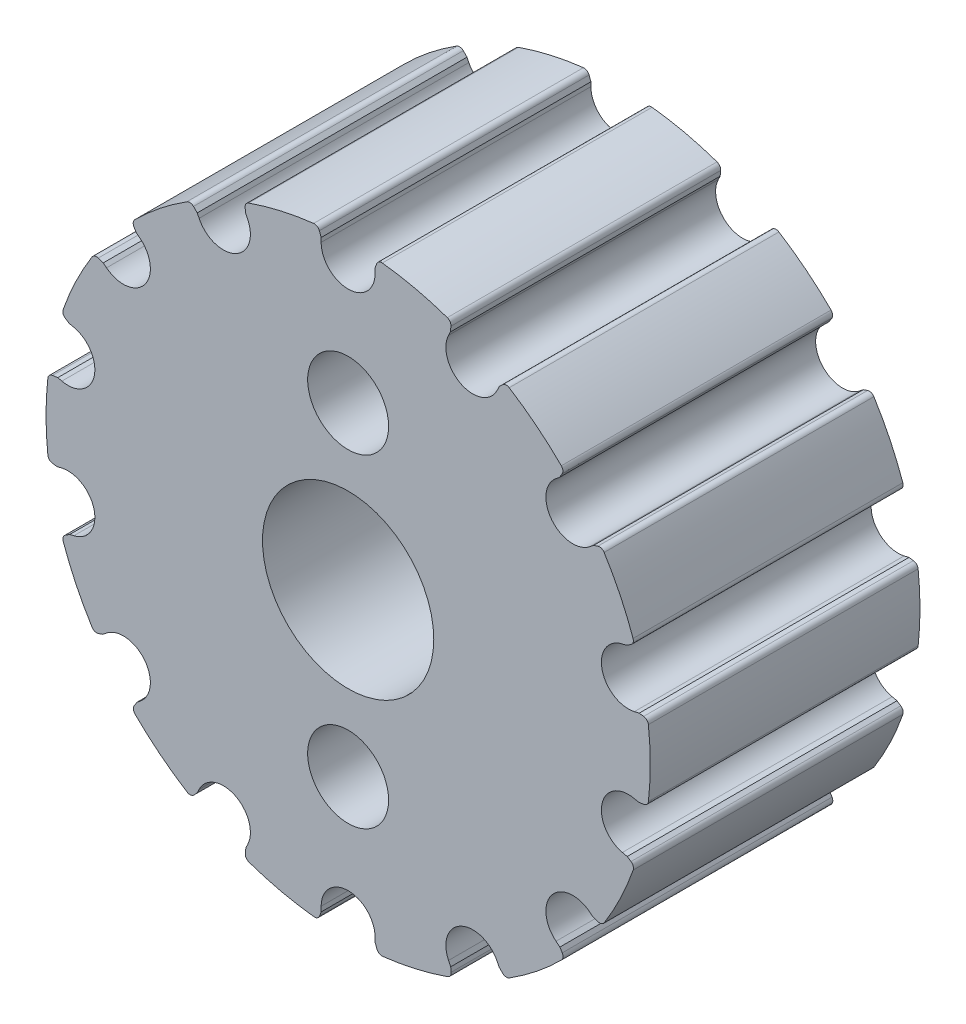
SolidWorks part; units mm, degrees
ref_plane "Спереди" through (0, 0, 0) normal (0, 0, 1) x (1, 0, 0)
ref_plane "Сверху" through (0, 0, 0) normal (0, 1, 0) x (1, 0, 0)
ref_plane "Справа" through (0, 0, 0) normal (1, 0, 0) x (0, 0, -1)
sketch "Эскиз1" plane through (0, 0, 0) normal (0, 0, 1) x (1, 0, 0)
  line L0 (0, 0) -> (0, 13.132) construction
  line L1 (-0.6859, 9.95) -> (0, 9.95)
  line L2 (0, 9.95) -> (0.676, 9.95)
  line L3 (-0.6859, 9.95) -> (-1.1204, 11.1438)
  line L4 (0, 11.2) -> (1.7516, 11.2) construction
  line L5 (3.6991, 9.2623) -> (3.8256, 10.5264)
  line L6 (1.1109, 11.1448) -> (0.676, 9.95)
  line L7 (3.6991, 9.2623) -> (4.3171, 8.9646)
  line L8 (4.3171, 8.9646) -> (4.9262, 8.6713)
  line L9 (5.8364, 9.5591) -> (4.9262, 8.6713)
  line L10 (7.3516, 6.74) -> (8.014, 7.8241)
  line L11 (7.3516, 6.74) -> (7.7792, 6.2037)
  line L12 (7.7792, 6.2037) -> (8.2007, 5.6752)
  line L13 (9.4059, 6.0801) -> (8.2007, 5.6752)
  line L14 (9.5479, 2.8828) -> (10.6151, 3.5721)
  line L15 (9.5479, 2.8828) -> (9.7005, 2.2141)
  line L16 (9.7005, 2.2141) -> (9.851, 1.555)
  line L17 (11.1125, 1.3969) -> (9.851, 1.555)
  line L18 (9.8532, -1.5453) -> (11.1137, -1.3874)
  line L19 (9.8532, -1.5453) -> (9.7005, -2.2141)
  line L20 (9.7005, -2.2141) -> (9.5501, -2.8731)
  line L21 (10.6182, -3.563) -> (9.5501, -2.8731)
  line L22 (8.2069, -5.6674) -> (9.4112, -6.0721)
  line L23 (8.2069, -5.6674) -> (7.7792, -6.2037)
  line L24 (7.7792, -6.2037) -> (7.3577, -6.7322)
  line L25 (8.0207, -7.8172) -> (7.3577, -6.7322)
  line L26 (4.9351, -8.667) -> (5.8446, -9.5541)
  line L27 (4.9351, -8.667) -> (4.3171, -8.9646)
  line L28 (4.3171, -8.9646) -> (3.7081, -9.2579)
  line L29 (3.8347, -10.5231) -> (3.7081, -9.2579)
  line L30 (0.6859, -9.95) -> (1.1204, -11.1438)
  line L31 (0.6859, -9.95) -> (0, -9.95)
  line L32 (0, -9.95) -> (-0.676, -9.95)
  line L33 (-1.1109, -11.1448) -> (-0.676, -9.95)
  line L34 (-3.6991, -9.2623) -> (-3.8256, -10.5264)
  line L35 (-3.6991, -9.2623) -> (-4.3171, -8.9646)
  line L36 (-4.3171, -8.9646) -> (-4.9262, -8.6713)
  line L37 (-5.8364, -9.5591) -> (-4.9262, -8.6713)
  line L38 (-7.3516, -6.74) -> (-8.014, -7.8241)
  line L39 (-7.3516, -6.74) -> (-7.7792, -6.2037)
  line L40 (-7.7792, -6.2037) -> (-8.2007, -5.6752)
  line L41 (-9.4059, -6.0801) -> (-8.2007, -5.6752)
  line L42 (-9.5479, -2.8828) -> (-10.6151, -3.5721)
  line L43 (-9.5479, -2.8828) -> (-9.7005, -2.2141)
  line L44 (-9.7005, -2.2141) -> (-9.851, -1.555)
  line L45 (-11.1125, -1.3969) -> (-9.851, -1.555)
  line L46 (-9.8532, 1.5453) -> (-11.1137, 1.3874)
  line L47 (-9.8532, 1.5453) -> (-9.7005, 2.2141)
  line L48 (-9.7005, 2.2141) -> (-9.5501, 2.8731)
  line L49 (-10.6182, 3.563) -> (-9.5501, 2.8731)
  line L50 (-8.2069, 5.6674) -> (-9.4112, 6.0721)
  line L51 (-8.2069, 5.6674) -> (-7.7792, 6.2037)
  line L52 (-7.7792, 6.2037) -> (-7.3577, 6.7322)
  line L53 (-8.0207, 7.8172) -> (-7.3577, 6.7322)
  line L54 (-4.9351, 8.667) -> (-5.8446, 9.5541)
  line L55 (-4.9351, 8.667) -> (-4.3171, 8.9646)
  line L56 (-4.3171, 8.9646) -> (-3.7081, 9.2579)
  line L57 (-3.8347, 10.5231) -> (-3.7081, 9.2579)
  line L114 (0, 9.95) -> (0, 22.3219) construction
  arc A0 (3.8256, 10.5264) -> (1.1109, 11.1448) centre (0, 0) ccw
  circle A1 centre (0, 0) radius 2.5
  circle A2 centre (0, 6) radius 1.5
  circle A3 centre (0, -6) radius 1.5
  arc A4 (8.014, 7.8241) -> (5.8364, 9.5591) centre (0, 0) ccw
  arc A5 (10.6151, 3.5721) -> (9.4059, 6.0801) centre (0, 0) ccw
  arc A6 (11.1137, -1.3874) -> (11.1125, 1.3969) centre (0, 0) ccw
  arc A7 (9.4112, -6.0721) -> (10.6182, -3.563) centre (0, 0) ccw
  arc A8 (5.8446, -9.5541) -> (8.0207, -7.8172) centre (0, 0) ccw
  arc A9 (1.1204, -11.1438) -> (3.8347, -10.5231) centre (0, 0) ccw
  arc A10 (-3.8256, -10.5264) -> (-1.1109, -11.1448) centre (0, 0) ccw
  arc A11 (-8.014, -7.8241) -> (-5.8364, -9.5591) centre (0, 0) ccw
  arc A12 (-10.6151, -3.5721) -> (-9.4059, -6.0801) centre (0, 0) ccw
  arc A13 (-11.1137, 1.3874) -> (-11.1125, -1.3969) centre (0, 0) ccw
  arc A14 (-9.4112, 6.0721) -> (-10.6182, 3.563) centre (0, 0) ccw
  arc A15 (-5.8446, 9.5541) -> (-8.0207, 7.8172) centre (0, 0) ccw
  arc A16 (-1.1204, 11.1438) -> (-3.8347, 10.5231) centre (0, 0) ccw
  dimension "D4" = 40
  dimension "D6" = 1.25
  dimension "D7" = 22.4
  dimension "D8" = 6
  dimension "D3" = 0.676
  dimension "D5" = 110
extrude "Вытянуть1" add sketch "Эскиз1" along normal blind 10
fillet "Скругление1" radius 0.2 55 edges at (-9.5479, -2.8828, 5) (-10.6151, -3.5721, 5) (-7.3516, -6.74, 5) (-8.014, -7.8241, 5) (-11.1125, -1.3969, 5) (-9.851, -1.555, 5) (-9.4059, -6.0801, 5) (-8.2007, -5.6752, 5) (-5.8364, -9.5591, 5) (-4.9262, -8.6713, 5) (-3.6991, -9.2623, 5) (-3.8256, -10.5264, 5) (1.1204, -11.1438, 5) (0.6859, -9.95, 5) (-1.1109, -11.1448, 5) (-0.676, -9.95, 5) (4.9351, -8.667, 5) (5.8446, -9.5541, 5) (3.8347, -10.5231, 5) (3.7081, -9.2579, 5) (8.0207, -7.8172, 5) (7.3577, -6.7322, 5) (8.2069, -5.6674, 5) (9.4112, -6.0721, 5) (9.8532, -1.5453, 5) (11.1137, -1.3874, 5) (10.6182, -3.563, 5) (9.5501, -2.8731, 5) (11.1125, 1.3969, 5) (9.851, 1.555, 5) (9.5479, 2.8828, 5) (10.6151, 3.5721, 5) (8.014, 7.8241, 5) (7.3516, 6.74, 5) (9.4059, 6.0801, 5) (8.2007, 5.6752, 5) (3.6991, 9.2623, 5) (3.8256, 10.5264, 5) (5.8364, 9.5591, 5) (4.9262, 8.6713, 5) (-0.6859, 9.95, 5) (-1.1204, 11.1438, 5) (1.1109, 11.1448, 5) (0.676, 9.95, 5) (-4.9351, 8.667, 5) (-5.8446, 9.5541, 5) (-3.8347, 10.5231, 5) (-3.7081, 9.2579, 5) (-8.0207, 7.8172, 5) (-7.3577, 6.7322, 5) (-11.1137, 1.3874, 5) (-9.8532, 1.5453, 5) (-10.6182, 3.563, 5) (-9.4112, 6.0721, 5) (-8.2069, 5.6674, 5)
sketch "Эскиз2" plane through (0, 0, 10) normal (0, 0, 1) x (1, 0, 0)
  line L0 (0, 0) -> (0, 13.8774) construction
  line L1 (4.7401, 12.1477) -> (6.542, 11.2799)
  line L2 (-1, 13.0013) -> (1, 13.0013)
  line L3 (-1, 13.0013) -> (-1, 10.6564)
  line L4 (4.7401, 12.1477) -> (3.7227, 10.035)
  line L5 (1, 13.0013) -> (1, 10.6564)
  line L6 (6.542, 11.2799) -> (5.5246, 9.1672)
  line L7 (9.5414, 8.888) -> (10.7884, 7.3244)
  line L8 (9.5414, 8.888) -> (7.708, 7.426)
  line L9 (10.7884, 7.3244) -> (8.955, 5.8623)
  line L10 (12.4529, 3.868) -> (12.8979, 1.9181)
  line L11 (12.4529, 3.868) -> (10.1667, 3.3462)
  line L12 (12.8979, 1.9181) -> (10.6117, 1.3963)
  line L13 (12.8979, -1.9181) -> (12.4529, -3.868)
  line L14 (12.8979, -1.9181) -> (10.6117, -1.3963)
  line L15 (12.4529, -3.868) -> (10.1667, -3.3462)
  line L16 (10.7884, -7.3244) -> (9.5414, -8.888)
  line L17 (10.7884, -7.3244) -> (8.955, -5.8623)
  line L18 (9.5414, -8.888) -> (7.708, -7.426)
  line L19 (6.542, -11.2799) -> (4.7401, -12.1477)
  line L20 (6.542, -11.2799) -> (5.5246, -9.1672)
  line L21 (4.7401, -12.1477) -> (3.7227, -10.035)
  line L22 (1, -13.0013) -> (-1, -13.0013)
  line L23 (1, -13.0013) -> (1, -10.6564)
  line L24 (-1, -13.0013) -> (-1, -10.6564)
  line L25 (-4.7401, -12.1477) -> (-6.542, -11.2799)
  line L26 (-4.7401, -12.1477) -> (-3.7227, -10.035)
  line L27 (-6.542, -11.2799) -> (-5.5246, -9.1672)
  line L28 (-9.5414, -8.888) -> (-10.7884, -7.3244)
  line L29 (-9.5414, -8.888) -> (-7.708, -7.426)
  line L30 (-10.7884, -7.3244) -> (-8.955, -5.8623)
  line L31 (-12.4529, -3.868) -> (-12.8979, -1.9181)
  line L32 (-12.4529, -3.868) -> (-10.1667, -3.3462)
  line L33 (-12.8979, -1.9181) -> (-10.6117, -1.3963)
  line L34 (-12.8979, 1.9181) -> (-12.4529, 3.868)
  line L35 (-12.8979, 1.9181) -> (-10.6117, 1.3963)
  line L36 (-12.4529, 3.868) -> (-10.1667, 3.3462)
  line L37 (-10.7884, 7.3244) -> (-9.5414, 8.888)
  line L38 (-10.7884, 7.3244) -> (-8.955, 5.8623)
  line L39 (-9.5414, 8.888) -> (-7.708, 7.426)
  line L40 (-6.542, 11.2799) -> (-4.7401, 12.1477)
  line L41 (-6.542, 11.2799) -> (-5.5246, 9.1672)
  line L42 (-4.7401, 12.1477) -> (-3.7227, 10.035)
  arc A0 (-1, 10.6564) -> (1, 10.6564) centre (0, 10.6564) ccw
  arc A1 (3.7227, 10.035) -> (5.5246, 9.1672) centre (4.6236, 9.6011) ccw
  arc A2 (7.708, 7.426) -> (8.955, 5.8623) centre (8.3315, 6.6442) ccw
  arc A3 (10.1667, 3.3462) -> (10.6117, 1.3963) centre (10.3892, 2.3713) ccw
  arc A4 (10.6117, -1.3963) -> (10.1667, -3.3462) centre (10.3892, -2.3713) ccw
  arc A5 (8.955, -5.8623) -> (7.708, -7.426) centre (8.3315, -6.6442) ccw
  arc A6 (5.5246, -9.1672) -> (3.7227, -10.035) centre (4.6236, -9.6011) ccw
  arc A7 (1, -10.6564) -> (-1, -10.6564) centre (0, -10.6564) ccw
  arc A8 (-3.7227, -10.035) -> (-5.5246, -9.1672) centre (-4.6236, -9.6011) ccw
  arc A9 (-7.708, -7.426) -> (-8.955, -5.8623) centre (-8.3315, -6.6442) ccw
  arc A10 (-10.1667, -3.3462) -> (-10.6117, -1.3963) centre (-10.3892, -2.3713) ccw
  arc A11 (-10.6117, 1.3963) -> (-10.1667, 3.3462) centre (-10.3892, 2.3713) ccw
  arc A12 (-8.955, 5.8623) -> (-7.708, 7.426) centre (-8.3315, 6.6442) ccw
  arc A13 (-5.5246, 9.1672) -> (-3.7227, 10.035) centre (-4.6236, 9.6011) ccw
  dimension "D1" = 1
  dimension "D2" = 1
extrude "Вырез-Вытянуть1" cut sketch "Эскиз2" against normal blind 10
sketch "Эскиз3" plane through (0, 0, 10) normal (0, 0, 1) x (1, 0, 0)
  circle A0 centre (0, 0) radius 3.175
extrude "Вырез-Вытянуть2" cut sketch "Эскиз3" against normal blind 10
